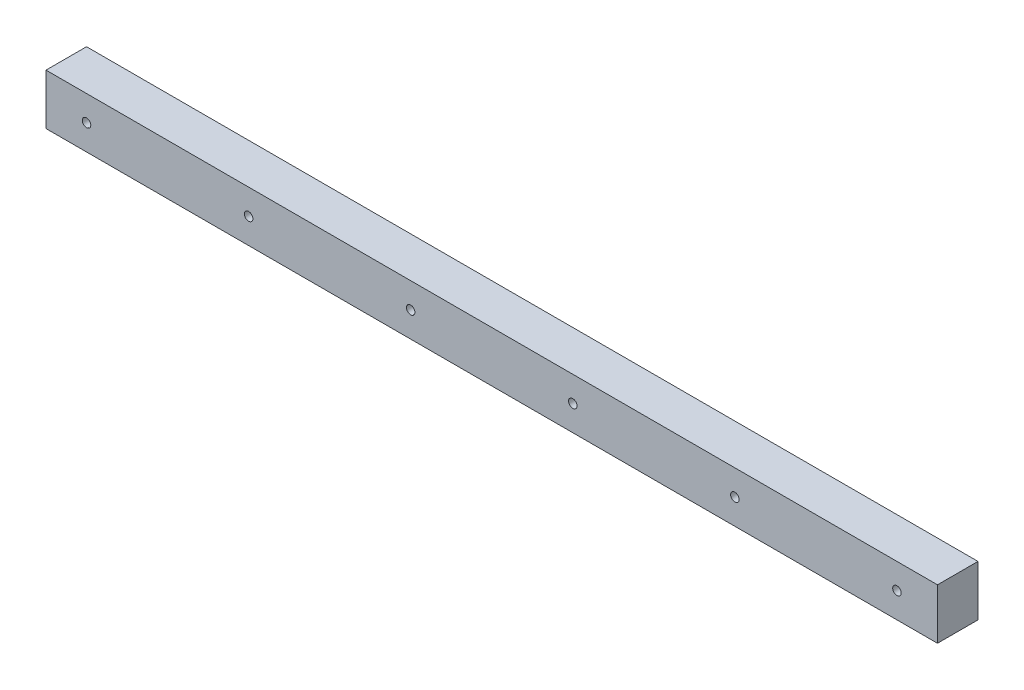
SolidWorks part; units mm, degrees
ref_plane "Front Plane" through (0, 0, 0) normal (0, 0, 1) x (1, 0, 0)
ref_plane "Top Plane" through (0, 0, 0) normal (0, 1, 0) x (1, 0, 0)
ref_plane "Right Plane" through (0, 0, 0) normal (1, 0, 0) x (0, 0, -1)
sketch "Sketch1" plane through (0, 0, 0) normal (0, 1, 0) x (1, 0, 0)
  line L1 (-220, 10) -> (220, 10)
  line L2 (-220, 10) -> (-220, -10)
  line L3 (-220, -10) -> (220, -10)
  line L4 (220, 10) -> (220, -10)
  line L5 (-220, 10) -> (220, -10) construction
  line L6 (-220, -10) -> (220, 10) construction
  point P0 (0, 0)
  dimension "D1" = 440
  dimension "D2" = 20
extrude "Boss-Extrude1" add sketch "Sketch1" along normal blind 25
hole_wizard "M5 Tapped Hole1" positions "Sketch4" profile "Sketch3" tap size "M5" standard "ISO"
sketch "Sketch4" plane through (0, 0, -10) normal (0, 0, -1) x (-1, 0, 0)
  line L0 (0, 0) -> (0, 25) construction
  line L1 (-220, 25) -> (220, 25) construction
  point P0 (0, 12.5)
  point P11 (0, 12.5)
  point P17 (60, 12.5)
  point P18 (120, 12.5)
  point P19 (180, 12.5)
  point P24 (-60, 12.5)
  point P25 (-120, 12.5)
  point P26 (-180, 12.5)
  dimension "D1" = 4
  dimension "D2" = 4
sketch "Sketch3" plane through (0, 12.5, -10) normal (1, 0, 0) x (0, 1, 0)
  line L0 (0, 0) -> (0, 16.2618)
  line L1 (0, 16.2618) -> (2.1, 15)
  line L2 (2.1, 15) -> (2.1, 0)
  line L5 (2.1, 0) -> (0, 0)
  line L10 (0, 16.2618) -> (-2.1, 15) construction
  line L11 (0, -6.35) -> (0, 107.95) construction
  dimension "Tap Drill Dia." = 4.2
  dimension "Tap Drill Depth" = 15
  dimension "Drill Angle" = 118
cosmetic thread "Hole Thread1" parameters "D1"=10, "D2"=5
cosmetic thread "Hole Thread2" parameters "D1"=10, "D2"=5
cosmetic thread "Hole Thread3" parameters "D1"=10, "D2"=5
cosmetic thread "Hole Thread4" parameters "D1"=10, "D2"=5
cosmetic thread "Hole Thread5" parameters "D1"=10, "D2"=5
cosmetic thread "Hole Thread6" parameters "D1"=10, "D2"=5
cosmetic thread "Hole Thread7" parameters "D1"=10, "D2"=5
hole_wizard "M5 Tapped Hole2" positions "Sketch5" profile "Sketch6" tap size "M5" standard "ISO"
sketch "Sketch5" plane through (0, 0, 10) normal (0, 0, 1) x (1, 0, 0)
  line L0 (0, 0) -> (0, 25) construction
  line L1 (-220, 25) -> (220, 25) construction
  point P0 (40, 12.5)
  point P14 (120, 12.5)
  point P15 (200, 12.5)
  point P22 (-40, 12.5)
  point P23 (-120, 12.5)
  point P24 (-200, 12.5)
  point P25 (0, 0)
  point P26 (0, 12.5)
  dimension "D1" = 40
  dimension "D2" = 3
  dimension "D3" = 4
cosmetic thread "Hole Thread8" parameters "D1"=20, "D2"=5
cosmetic thread "Hole Thread9" parameters "D1"=20, "D2"=5
cosmetic thread "Hole Thread10" parameters "D1"=20, "D2"=5
cosmetic thread "Hole Thread11" parameters "D1"=20, "D2"=5
cosmetic thread "Hole Thread12" parameters "D1"=20, "D2"=5
cosmetic thread "Hole Thread13" parameters "D1"=20, "D2"=5
sketch "Sketch6" plane through (40, 12.5, 10) normal (1, 0, 0) x (0, -1, 0)
  line L0 (0, 0) -> (0, 16.2618)
  line L1 (0, 16.2618) -> (2.1, 15)
  line L2 (2.1, 15) -> (2.1, 0)
  line L5 (2.1, 0) -> (0, 0)
  line L10 (0, 16.2618) -> (-2.1, 15) construction
  line L11 (0, -6.35) -> (0, 107.95) construction
  dimension "Tap Drill Dia." = 4.2
  dimension "Tap Drill Depth" = 15
  dimension "Drill Angle" = 118
